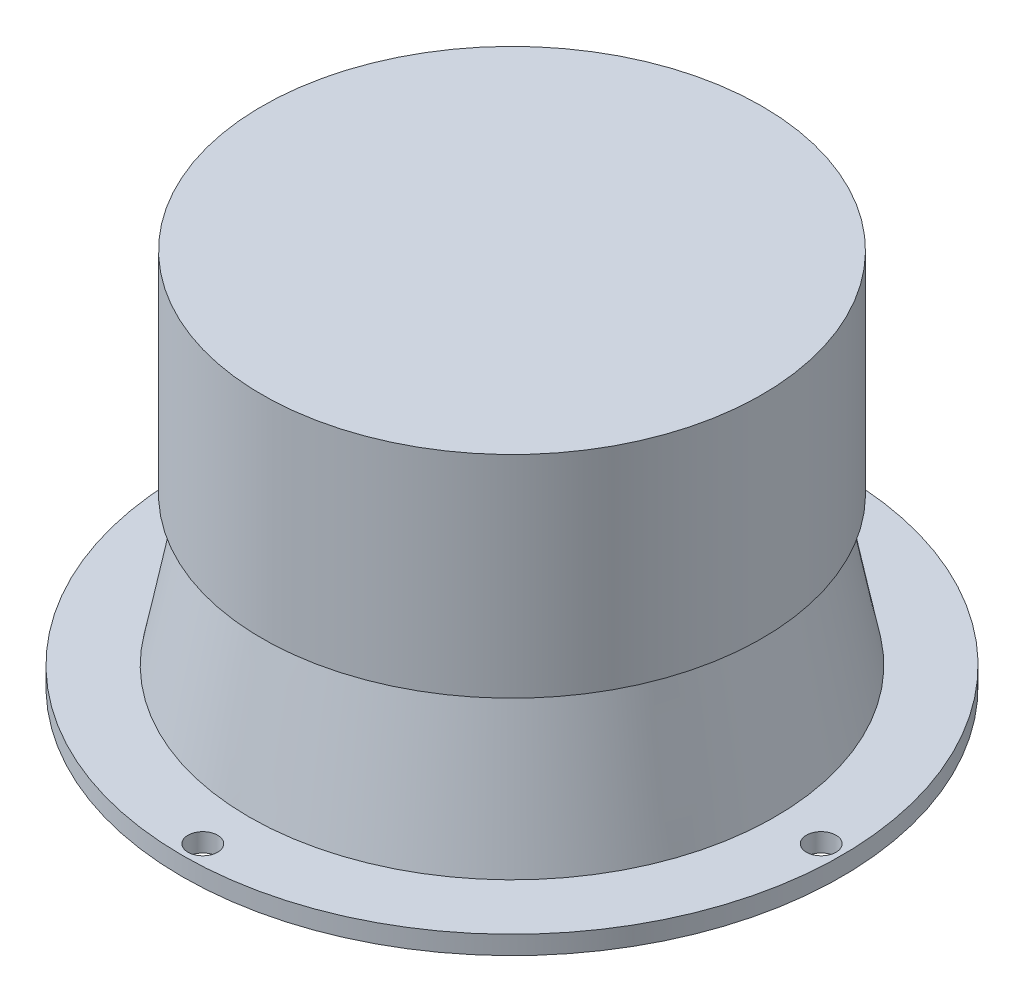
SolidWorks part; units mm, degrees
ref_plane "Front Plane" through (0, 0, 0) normal (0, 0, 1) x (1, 0, 0)
ref_plane "Top Plane" through (0, 0, 0) normal (0, 1, 0) x (1, 0, 0)
ref_plane "Right Plane" through (0, 0, 0) normal (1, 0, 0) x (0, 0, -1)
sketch "Sketch1" plane through (0, 0, 0) normal (0, 1, 0) x (1, 0, 0)
  circle A0 centre (0, 0) radius 44.5
  circle A1 centre (0, 0) radius 41.75 construction
  circle A2 centre (0, 41.75) radius 2
  circle A3 centre (41.75, 0) radius 2
  circle A4 centre (0, -41.75) radius 2
  circle A5 centre (-41.75, 0) radius 2
  point P15 (0, 0)
  dimension "D1" = 4
  dimension "D2" = 83.5
  dimension "D3" = 89
  dimension "D4" = 4
extrude "Boss-Extrude1" add sketch "Sketch1" along normal blind 2.5
sketch "Sketch2" plane through (0, 0, 0) normal (0, -1, 0) x (-1, 0, 0)
  circle A0 centre (0, 0) radius 34
  dimension "D1" = 68
extrude "Boss-Extrude2" add sketch "Sketch2" along normal blind 1
sketch "Sketch3" plane through (0, 2.5, 0) normal (0, 1, 0) x (1, 0, 0)
  circle A0 centre (0, 0) radius 35.5
  dimension "D1" = 71
extrude "Boss-Extrude3" add sketch "Sketch3" along normal blind 20 draft 11
sketch "Sketch4" plane through (0, 22.5, 0) normal (0, 1, 0) x (1, 0, 0)
  circle A0 centre (0, 0) radius 33.75
  dimension "D1" = 67.5
extrude "Boss-Extrude4" add sketch "Sketch4" along normal blind 28.5
